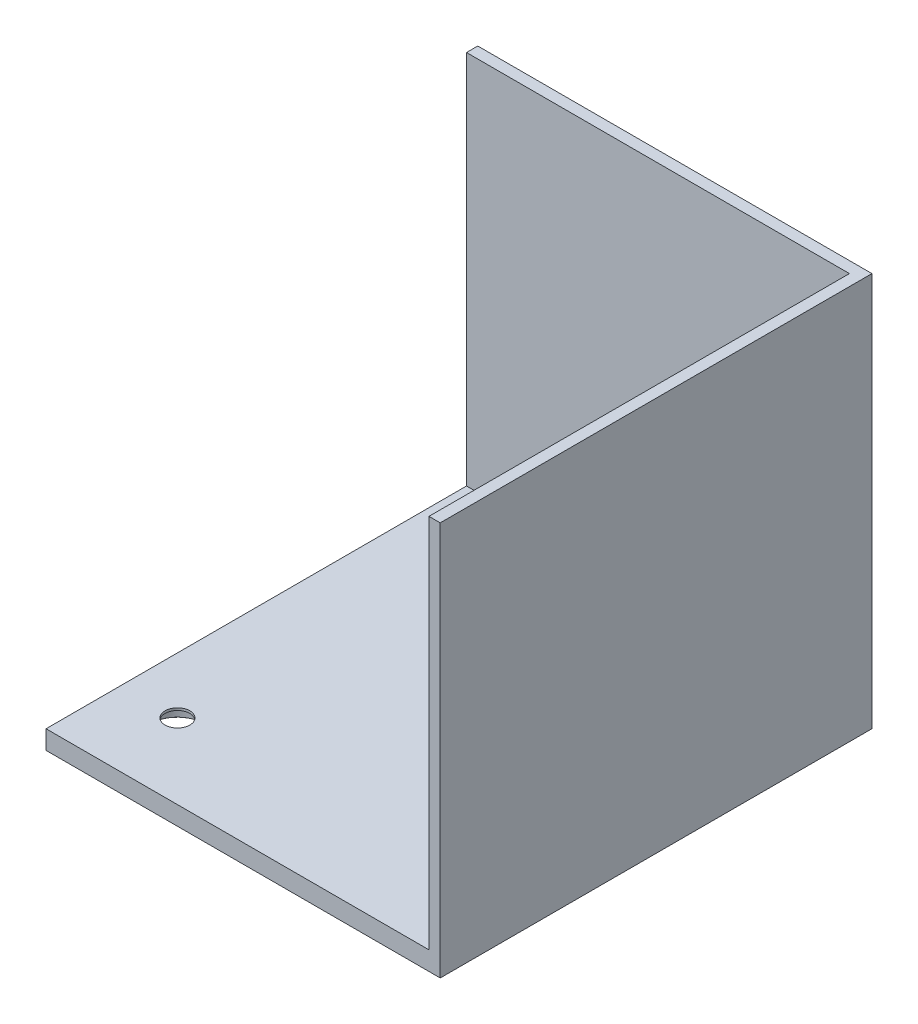
SolidWorks part; units mm, degrees
ref_plane "Front Plane" through (0, 0, 0) normal (0, 0, 1) x (1, 0, 0)
ref_plane "Top Plane" through (0, 0, 0) normal (0, 1, 0) x (1, 0, 0)
ref_plane "Right Plane" through (0, 0, 0) normal (1, 0, 0) x (0, 0, -1)
sketch "Sketch3" plane through (0, 0, 0) normal (0, 1, 0) x (1, 0, 0)
  line L1 (-52.5, -57.5) -> (52.5, -57.5)
  line L2 (-52.5, -57.5) -> (-52.5, 57.5)
  line L3 (-52.5, 57.5) -> (52.5, 57.5)
  line L4 (52.5, -57.5) -> (52.5, 57.5)
  line L5 (-52.5, -57.5) -> (52.5, 57.5) construction
  line L6 (-52.5, 57.5) -> (52.5, -57.5) construction
  point P0 (0, 0)
extrude "Boss-Extrude1" add sketch "Sketch3" along normal blind 105
sketch "Sketch6" plane through (0, 105, 0) normal (0, 1, 0) x (1, 0, 0)
  line L1 (49.5, 54.5) -> (-52.5, 54.5)
  line L2 (49.5, 54.5) -> (49.5, -57.5)
  line L3 (49.5, -57.5) -> (-52.5, -57.5)
  line L4 (-52.5, 54.5) -> (-52.5, -57.5)
extrude "Cut-Extrude1" cut sketch "Sketch6" against normal blind 100
hole_wizard "CBORE for M6 Hex Head Bolt1" positions "3DSketch1" profile "Sketch7" counterbore size "M6" standard "ANSI Metric" end condition through all
sketch3d "3DSketch1"
  point P0 (37.5, 0, 37.5)
  point P2 (37.5, 0, -37.5)
  point P4 (-37.5, 0, -37.5)
  point P6 (-37.5, 0, 37.5)
  point P9 (0, 0, 0)
  point P10 (0, 0, 0)
  point P11 (0, 0, 0)
  point P12 (0, 0, 0)
sketch "Sketch7" plane through (37.5, 0, 37.5) normal (1, 0, 0) x (0, 0, -1)
  line L0 (0, 0) -> (0, 105)
  line L1 (0, 105) -> (3.3, 105)
  line L3 (3.3, 105) -> (3.3, 4.38)
  line L4 (7.275, 4.38) -> (3.3, 4.38)
  line L5 (7.275, 4.38) -> (7.275, 0.025)
  line L6 (7.275, 0.025) -> (7.3, 0)
  line L7 (7.3, 0) -> (0, 0)
  line L8 (-7.275, 0.025) -> (-7.3, 0) construction
  line L11 (0, -6.35) -> (0, 107.95) construction
  dimension "Thru Hole Dia." = 6.6
  dimension "Thru Hole Depth" = 105
  dimension "C'Bore Dia." = 14.55
  dimension "C'Bore Depth" = 4.38
  dimension "Near C'Sink Dia." = 14.6
  dimension "Near C'Sink Angle" = 90
